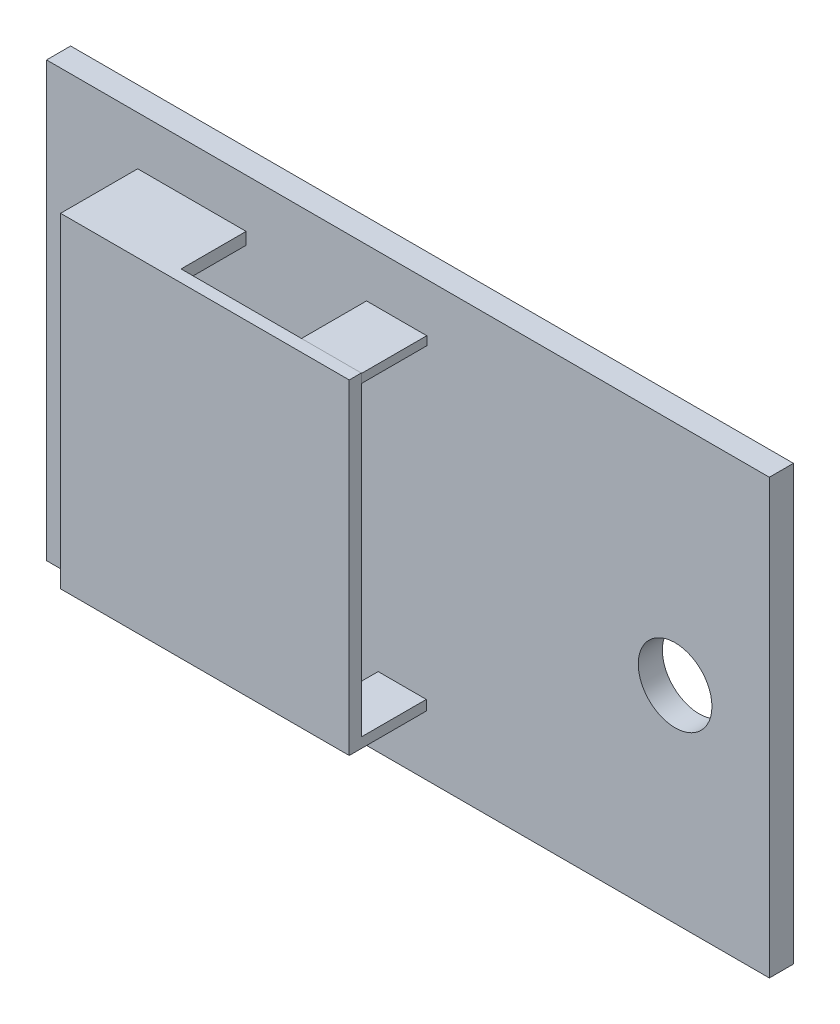
SolidWorks part; units mm, degrees
ref_plane "Front Plane" through (0, 0, 0) normal (0, 0, 1) x (1, 0, 0)
ref_plane "Top Plane" through (0, 0, 0) normal (0, 1, 0) x (1, 0, 0)
ref_plane "Right Plane" through (0, 0, 0) normal (1, 0, 0) x (0, 0, -1)
sketch "Sketch1" plane through (0, 0, 0) normal (0, 0, 1) x (1, 0, 0)
  line L1 (-99.3976, 33.4337) -> (200.6024, 33.4337)
  line L2 (-99.3976, 33.4337) -> (-99.3976, -146.5663)
  line L3 (-99.3976, -146.5663) -> (200.6024, -146.5663)
  line L4 (200.6024, 33.4337) -> (200.6024, -146.5663)
  circle A1 centre (161.4744, -60.8983) radius 15.2903
  dimension "D1" = 300
  dimension "D2" = 180
extrude "Boss-Extrude1" add sketch "Sketch1" along normal blind 10
ref_plane "Plane1" through (0, 0, 10) normal (0, 0, 1) x (1, 0, 0)
sketch "Sketch2" plane through (0, 0, 10) normal (0, 0, 1) x (1, 0, 0)
  line L2 (-61.567, 8.2147) -> (-61.567, -116.7853)
  line L4 (-56.567, 8.2147) -> (-56.567, -116.7853)
  line L9 (-56.567, 8.2147) -> (-16.567, 8.2147)
  line L11 (-56.567, 13.2147) -> (-16.567, 13.2147)
  line L12 (-16.567, 8.2147) -> (-16.567, 13.2147)
  line L13 (33.4143, 9.5832) -> (58.4143, 9.5832)
  line L14 (33.4143, 9.5832) -> (33.4143, 13.2086)
  line L15 (33.4143, 13.2086) -> (58.4143, 13.2086)
  line L16 (58.4143, 9.5832) -> (58.4143, 13.2086)
  line L17 (38.231, -121.7853) -> (58.231, -121.7853)
  line L18 (38.231, -121.7853) -> (38.231, -117.6124)
  line L19 (38.231, -117.6124) -> (58.231, -117.6124)
  line L20 (58.231, -121.7853) -> (58.231, -117.6124)
  line L22 (-61.567, -116.7853) -> (-61.567, -121.7853)
  line L23 (-61.567, -121.7853) -> (20.433, -121.7853)
  line L24 (20.433, -116.7853) -> (20.433, -121.7853)
  line L25 (-56.567, 13.2147) -> (-61.567, 13.2147)
  line L26 (-61.567, 13.2147) -> (-61.567, 8.2147)
  line L27 (-56.567, -116.7853) -> (20.433, -116.7853)
  dimension "D1" = 125
  dimension "D2" = 5
  dimension "D3" = 5
  dimension "D4" = 82
  dimension "D5" = 40
  dimension "D6" = 5
  dimension "D7" = 50
  dimension "D8" = 25
  dimension "D9" = 20
extrude "Boss-Extrude2" add sketch "Sketch2" along normal blind 27
ref_plane "Plane2" through (0, 0, 37) normal (0, 0, 1) x (1, 0, 0)
sketch "Sketch3" plane through (0, 0, 37) normal (0, 0, 1) x (1, 0, 0)
  line L1 (-61.567, 13.2147) -> (58.231, 13.2147)
  line L2 (-61.567, 13.2147) -> (-61.567, -121.7853)
  line L3 (-61.567, -121.7853) -> (58.231, -121.7853)
  line L4 (58.231, 13.2147) -> (58.231, -121.7853)
extrude "Boss-Extrude3" add sketch "Sketch3" along normal blind 5
